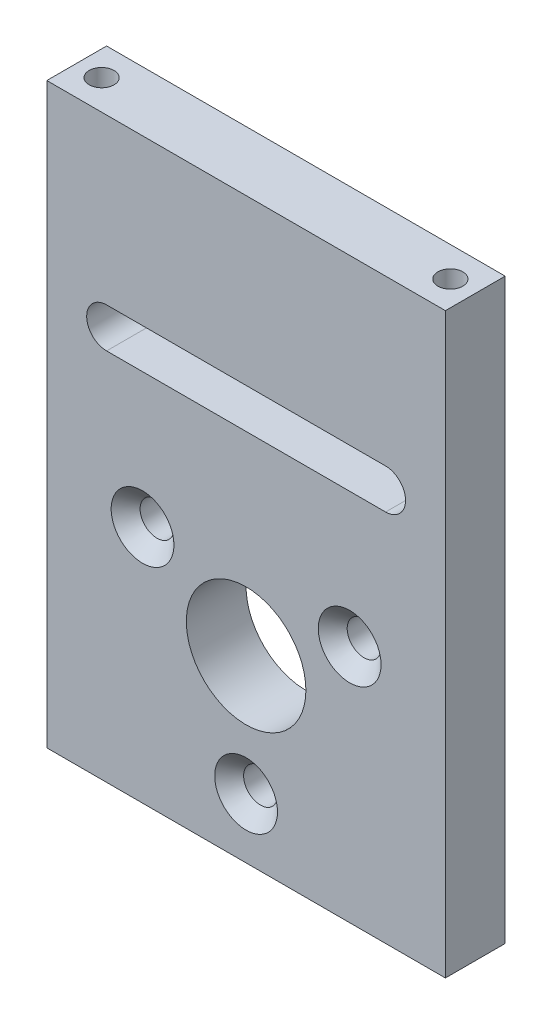
SolidWorks part; units mm, degrees
material "7075-T6 (SN)"
ref_plane "Front Plane" through (0, 0, 0) normal (0, 0, 1) x (1, 0, 0)
ref_plane "Top Plane" through (0, 0, 0) normal (0, 1, 0) x (1, 0, 0)
ref_plane "Right Plane" through (0, 0, 0) normal (1, 0, 0) x (0, 0, -1)
sketch "Sketch1" plane through (0, 0, 0) normal (0, 0, 1) x (1, 0, 0)
  line L1 (-20, -29) -> (20, -29)
  line L2 (-20, -29) -> (-20, 29)
  line L3 (-20, 29) -> (20, 29)
  line L4 (20, -29) -> (20, 29)
  line L5 (-20, -29) -> (20, 29) construction
  line L6 (-20, 29) -> (20, -29) construction
  point P0 (0, 0)
  dimension "D1" = 40
  dimension "D2" = 58
extrude "Boss-Extrude1" add sketch "Sketch1" along normal mid plane 6
sketch "Sketch2" plane through (0, 0, 3) normal (0, 0, 1) x (1, 0, 0)
  line L0 (-20, -29) -> (20, -29) construction
  line L1 (0, -55) -> (0, 55) construction
  circle A0 centre (0, -11) radius 6
  dimension "D1" = 12
  dimension "D2" = 18
extrude "Cut-Extrude1" cut sketch "Sketch2" against normal through all
hole_wizard "CSK for M3 Countersunk Flat Head Screw1" positions "Sketch3" profile "Sketch4" countersink size "M3" standard "ISO" end condition through all
sketch "Sketch3" plane through (0, 0, 3) normal (0, 0, 1) x (1, 0, 0)
  line L0 (0, -55) -> (0, 55) construction
  circle A0 centre (0, -11) radius 12 construction
  point P0 (0, -23)
  point P20 (-10.3923, -5)
  point P21 (10.3923, -5)
  dimension "D1" = 24
  dimension "D2" = 3
sketch "Sketch4" plane through (0, -23, 3) normal (1, 0, 0) x (0, -1, 0)
  line L0 (0, 0) -> (0, 6)
  line L1 (0, 6) -> (1.7, 6)
  line L2 (1.7, 6) -> (1.7, 1.45)
  line L3 (1.7, 1.45) -> (3.15, 0)
  line L5 (3.15, 0) -> (0, 0)
  line L6 (-1.7, 1.45) -> (-3.15, 0) construction
  line L11 (0, -6.35) -> (0, 107.95) construction
  dimension "Thru Hole Dia." = 3.4
  dimension "Thru Hole Depth" = 6
  dimension "Near C'Sink Dia." = 6.3
  dimension "Near C'Sink Angle" = 90
hole_wizard "Tap Drill for M3 Tap1" positions "Sketch5" profile "Sketch6" hole size "M3" standard "ISO"
sketch "Sketch5" plane through (0, -29, 0) normal (0, -1, 0) x (-1, 0, 0)
  line L0 (0, 3.3) -> (0, -3.3) construction
  line L1 (20, -3) -> (20, 3) construction
  point P0 (10.75, 0)
  point P2 (-10.75, 0)
  point P17 (20, 0)
  dimension "D1" = 21.5
  dimension "D2" = 10.75
sketch "Sketch6" plane through (-10.75, -29, 0) normal (1, 0, 0) x (0, 0, -1)
  line L0 (0, 0) -> (0, 9.7511)
  line L1 (0, 9.7511) -> (1.25, 9)
  line L2 (1.25, 9) -> (1.25, 0)
  line L5 (1.25, 0) -> (0, 0)
  line L10 (0, 9.7511) -> (-1.25, 9) construction
  line L11 (0, -6.35) -> (0, 107.95) construction
  dimension "Hole Dia." = 2.5
  dimension "Hole Depth" = 9
  dimension "Drill Angle" = 118
cosmetic thread "Cosmetic Thread3" parameters "D2"=3
cosmetic thread "Cosmetic Thread4" parameters "D2"=3
hole_wizard "Tap Drill for M3 Tap2" positions "Sketch7" profile "Sketch8" hole size "M3" standard "ISO"
sketch "Sketch7" plane through (0, 29, 0) normal (0, 1, 0) x (1, 0, 0)
  line L0 (20, -3) -> (20, 3) construction
  line L1 (0, -3.3) -> (0, 3.3) construction
  point P0 (17.5, 0)
  point P5 (20, 0)
  point P8 (-17.5, 0)
  dimension "D1" = 2.5
sketch "Sketch8" plane through (17.5, 29, 0) normal (1, 0, 0) x (0, 0, 1)
  line L0 (0, 0) -> (0, 9.7511)
  line L1 (0, 9.7511) -> (1.25, 9)
  line L2 (1.25, 9) -> (1.25, 0)
  line L5 (1.25, 0) -> (0, 0)
  line L10 (0, 9.7511) -> (-1.25, 9) construction
  line L11 (0, -6.35) -> (0, 107.95) construction
  dimension "Hole Dia." = 2.5
  dimension "Hole Depth" = 9
  dimension "Drill Angle" = 118
cosmetic thread "Cosmetic Thread1" parameters "D2"=3
cosmetic thread "Cosmetic Thread2" parameters "D2"=3
sketch "Sketch10" plane through (0, 0, 3) normal (0, 0, 1) x (1, 0, 0)
  line L0 (-14, 10.5) -> (14, 10.5) construction
  line L1 (-14, 12.5) -> (14, 12.5)
  line L2 (-14, 8.5) -> (14, 8.5)
  line L3 (20, 29) -> (-20, 29) construction
  line L4 (0, -3.3) -> (0, 3.3) construction
  arc A0 (-14, 12.5) -> (-14, 8.5) centre (-14, 10.5) ccw
  arc A1 (14, 8.5) -> (14, 12.5) centre (14, 10.5) ccw
  point P2 (0, 10.5)
  dimension "D1" = 16.5
  dimension "D2" = 4
  dimension "D3" = 28
extrude "Cut-Extrude3" cut sketch "Sketch10" against normal through all
sketch "Sketch9" plane through (0, 29, 0) normal (0, 1, 0) x (1, 0, 0)
  line L0 (20, 3) -> (-20, 3) construction
  line L1 (14, 3) -> (-14, 3)
  line L2 (14, 3) -> (14, -3)
  line L3 (14, -3) -> (-14, -3)
  line L4 (-14, 3) -> (-14, -3)
  line L5 (20, -3) -> (-20, -3) construction
  line L6 (20, -3) -> (20, 3) construction
  dimension "D1" = 6
  dimension "D2" = 28
extrude "Cut-Extrude2" [suppressed] cut sketch "Sketch9" against normal blind 21
equation "\"Screw_Diameter\"=24"
equation "\"D1@Sketch3\"=\"Screw_Diameter\""
equation "\"D2@Sketch5\"=\"D1@Sketch5\"/2"
